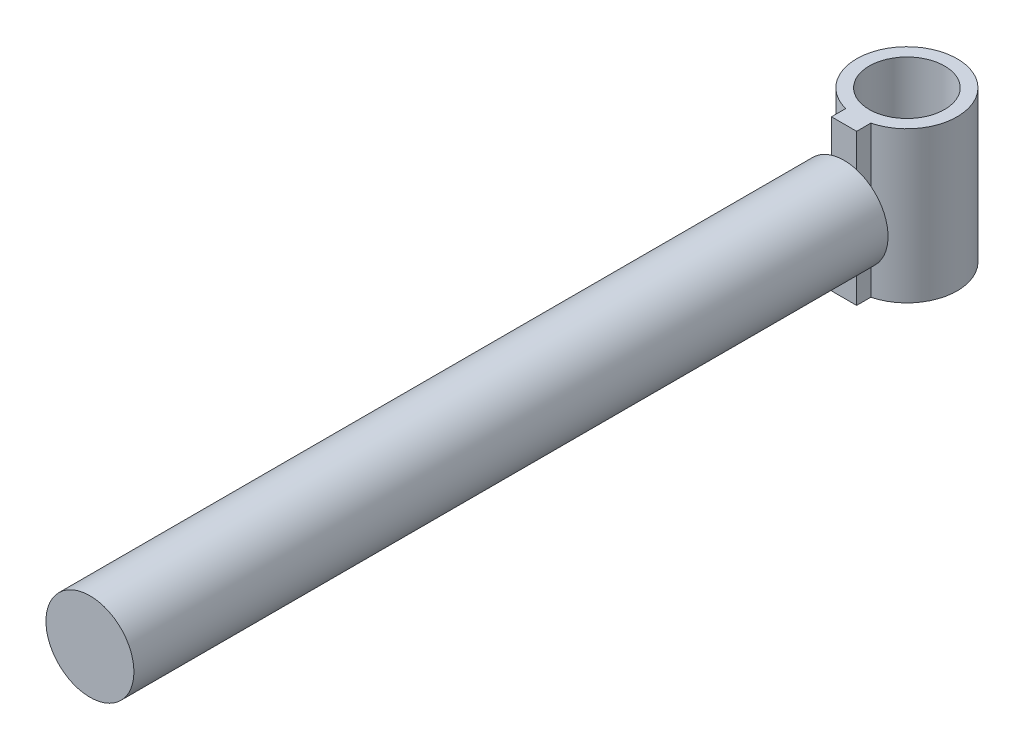
SolidWorks part; units mm, degrees
material "AISI 1020"
ref_plane "Ön Düzlem" through (0, 0, 0) normal (0, 0, 1) x (1, 0, 0)
ref_plane "Üst Düzlem" through (0, 0, 0) normal (0, 1, 0) x (1, 0, 0)
ref_plane "Sağ Düzlem" through (0, 0, 0) normal (1, 0, 0) x (0, 0, -1)
sketch "Çizim1" plane through (0, 0, 0) normal (0, 0, 1) x (1, 0, 0)
  circle A0 centre (0, 0) radius 35
  dimension "D1" = 70
extrude "Yükseklik-Ekstrüzyon1" add sketch "Çizim1" along normal blind 600
sketch "Çizim2" plane through (0, 0, 0) normal (0, 1, 0) x (1, 0, 0)
  line L0 (0, 0) -> (0, 50) construction
  line L1 (35, 0) -> (-35, 0) construction
  line L2 (10, 0) -> (10, 11.2702)
  line L3 (-10, 0) -> (-10, 11.2702)
  line L4 (-10, 0) -> (-10, 50) construction
  line L5 (10, 0) -> (10, 50) construction
  line L6 (-10, 0) -> (10, 0)
  circle A0 centre (0, 50) radius 30
  arc A1 (10, 11.2702) -> (-10, 11.2702) centre (0, 50) ccw
  dimension "D2" = 60
  dimension "D3" = 80
  dimension "D1" = 50
  dimension "D4" = 10
  dimension "D5" = 10
extrude "Yükseklik-Ekstrüzyon2" add sketch "Çizim2" along normal mid plane 120
